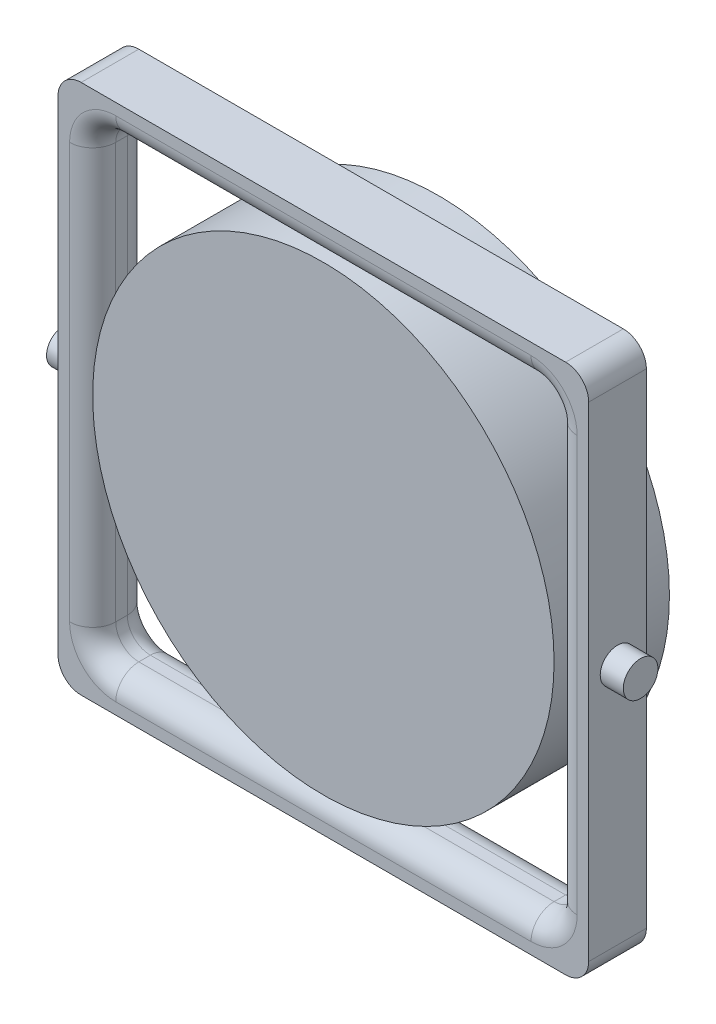
SolidWorks part; units mm, degrees
ref_plane "Front Plane" through (0, 0, 0) normal (0, 0, 1) x (1, 0, 0)
ref_plane "Top Plane" through (0, 0, 0) normal (0, 1, 0) x (1, 0, 0)
ref_plane "Right Plane" through (0, 0, 0) normal (1, 0, 0) x (0, 0, -1)
sketch "Sketch1" plane through (0, 0, 0) normal (0, 0, 1) x (1, 0, 0)
  line L1 (-23, -23) -> (23, -23)
  line L2 (-23, -23) -> (-23, 23)
  line L3 (-23, 23) -> (23, 23)
  line L4 (23, -23) -> (23, 23)
  line L5 (-23, -23) -> (23, 23) construction
  line L6 (-23, 23) -> (23, -23) construction
  point P0 (0, 0)
  dimension "D1" = 46
  dimension "D2" = 46
extrude "Boss-Extrude2" add sketch "Sketch1" along normal blind 5
sketch "Sketch3" plane through (0, 0, 5) normal (0, 0, 1) x (1, 0, 0)
  line L1 (-20, -20) -> (20, -20)
  line L2 (-20, -20) -> (-20, 20)
  line L3 (-20, 20) -> (20, 20)
  line L4 (20, -20) -> (20, 20)
  line L5 (-20, -20) -> (20, 20) construction
  line L6 (-20, 20) -> (20, -20) construction
  point P0 (0, 0)
  dimension "D1" = 40
  dimension "D2" = 40
extrude "Cut-Extrude1" cut sketch "Sketch3" against normal blind 15
fillet "Fillet1" radius 2 4 edges at (20, -20, 2.5) (-20, -20, 2.5) (-20, 20, 2.5) (20, 20, 2.5)
fillet "Fillet2" radius 2 12 edges at (0, -20, 0) (-19.4142, -19.4142, 0) (-20, 0, 0) (-19.4142, 19.4142, 0) (0, 20, 0) (19.4142, 19.4142, 0) (20, 0, 0) (-23, 23, 2.5) (-23, -23, 2.5) (23, -23, 2.5) (19.4142, -19.4142, 0) (23, 23, 2.5)
fillet "Fillet3" radius 2 8 edges at (-19.4142, 19.4142, 5) (0, 20, 5) (19.4142, 19.4142, 5) (20, 0, 5) (19.4142, -19.4142, 5) (0, -20, 5) (-19.4142, -19.4142, 5) (-20, 0, 5)
sketch "Sketch4" plane through (23, 0, 0) normal (1, 0, 0) x (0, 0, -1)
  line L0 (0, 0) -> (-5, 0)
  line L1 (0, -21) -> (0, 21) construction
  line L2 (-5, -21) -> (-5, 21) construction
  circle A0 centre (-2.5, 0) radius 1.5
  dimension "D1" = 3
extrude "Boss-Extrude3" add sketch "Sketch4" along normal blind 2 contours L0 A0 | L0 A0
mirror "Mirror1" about plane through (0, 0, 0) normal (1, 0, 0) of "Boss-Extrude3"
sketch "Sketch5" plane through (0, 0, 5) normal (0, 0, 1) x (1, 0, 0)
  circle A0 centre (0, 0) radius 20
  dimension "D1" = 40
extrude "Boss-Extrude4" add sketch "Sketch5" against normal blind 10 separate body
